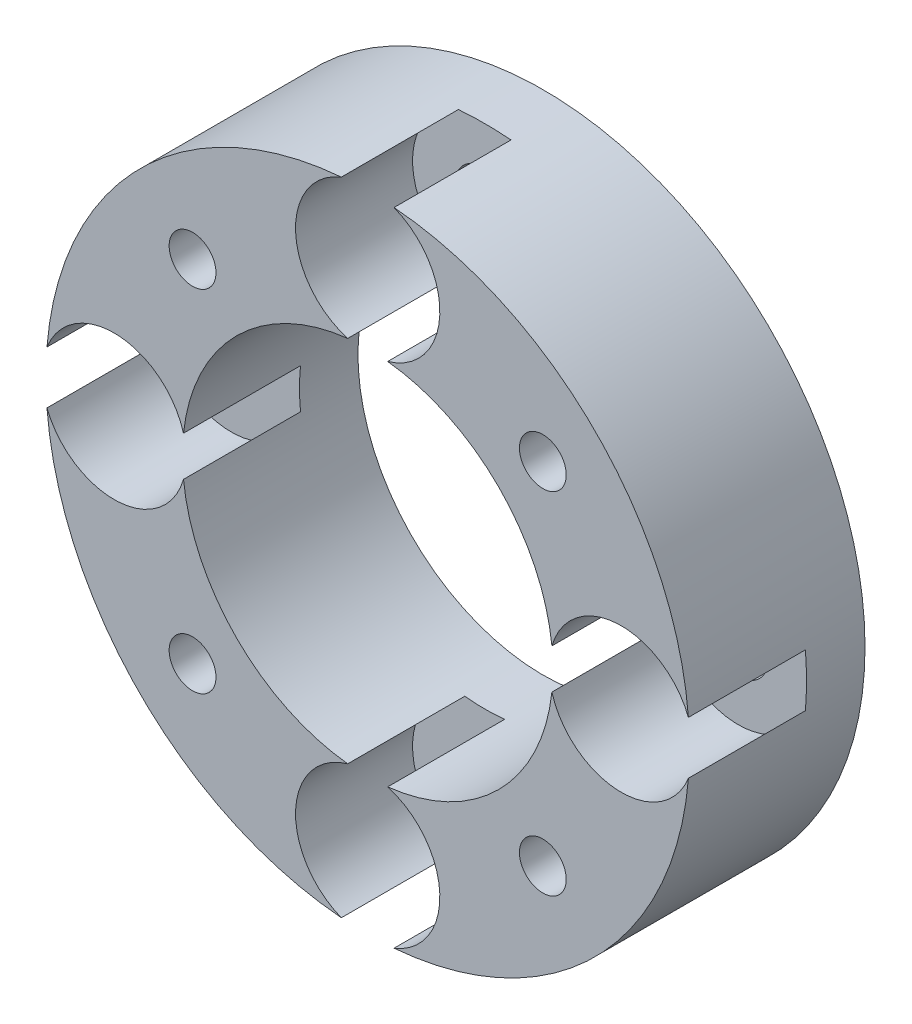
SolidWorks part; units mm, degrees
ref_plane "Front Plane" through (0, 0, 0) normal (0, 0, 1) x (1, 0, 0)
ref_plane "Top Plane" through (0, 0, 0) normal (0, 1, 0) x (1, 0, 0)
ref_plane "Right Plane" through (0, 0, 0) normal (1, 0, 0) x (0, 0, -1)
sketch "Sketch1" plane through (0, 0, 0) normal (0, 0, 1) x (1, 0, 0)
  line L0 (0, 0) -> (8.9803, 8.9803) construction
  circle A0 centre (0, 0) radius 12.7 construction
  circle A1 centre (8.9803, 8.9803) radius 1.2
  circle A2 centre (8.9803, -8.9803) radius 1.2
  circle A3 centre (-8.9803, -8.9803) radius 1.2
  circle A4 centre (-8.9803, 8.9803) radius 1.2
  circle A5 centre (0, 0) radius 9.5
  circle A6 centre (0, 0) radius 16.5
  circle A7 centre (0, 0) radius 13 construction
  circle A8 centre (0, 13) radius 1.55
  circle A9 centre (13, 0) radius 1.55
  circle A10 centre (0, -13) radius 1.55
  circle A11 centre (-13, 0) radius 1.55
  point P14 (0, 0)
  point P26 (0, 0)
  dimension "D1" = 4
  dimension "D2" = 4
extrude "Boss-Extrude1" add sketch "Sketch1" along normal blind 9
sketch "Sketch2" plane through (0, 0, 9) normal (0, 0, 1) x (1, 0, 0)
  circle A0 centre (0, 13) radius 3.7
  circle A1 centre (13, 0) radius 3.7
  circle A2 centre (0, -13) radius 3.7
  circle A3 centre (-13, 0) radius 3.7
  point P12 (0, 0)
  point P22 (0, 0)
  dimension "D1" = 4
extrude "Cut-Extrude1" cut sketch "Sketch2" against normal blind 6
